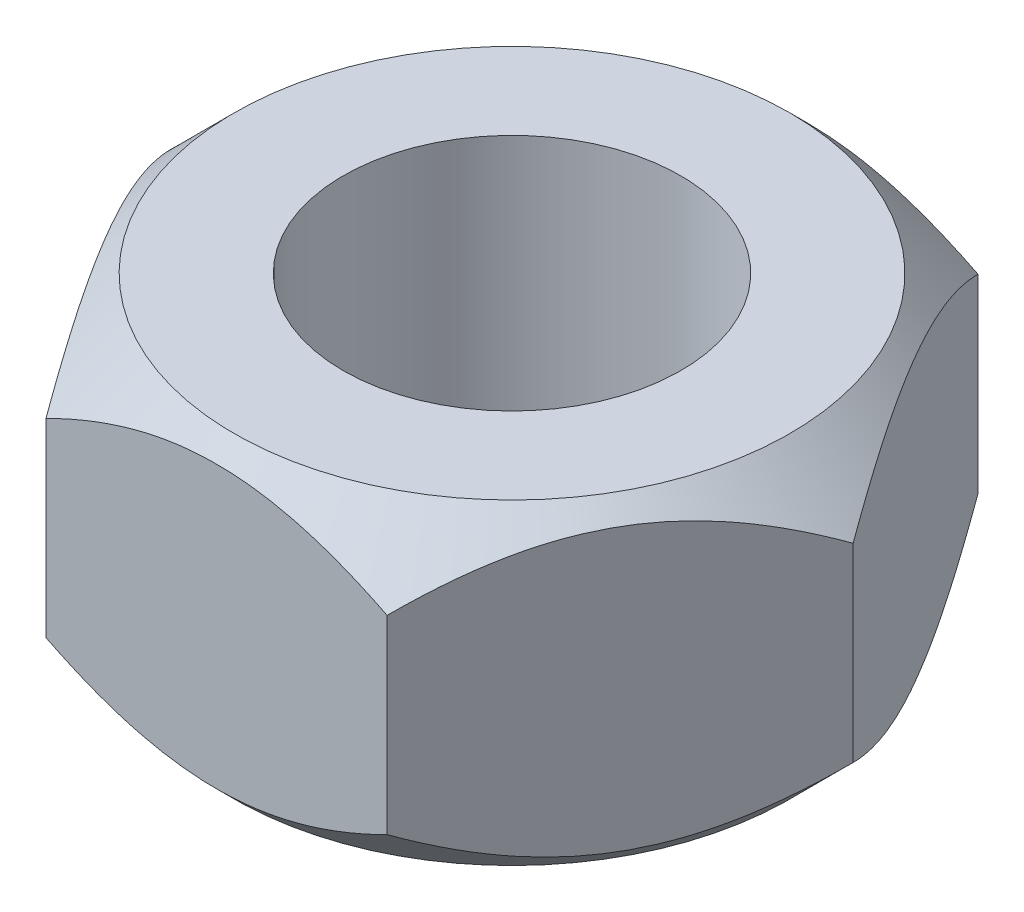
SolidWorks part; units mm, degrees
ref_plane "Front Plane" through (0, 0, 0) normal (0, 0, 1) x (1, 0, 0)
ref_plane "Top Plane" through (0, 0, 0) normal (0, 1, 0) x (1, 0, 0)
ref_plane "Right Plane" through (0, 0, 0) normal (1, 0, 0) x (0, 0, -1)
sketch "Sketch1" plane through (0, 0, 0) normal (0, 1, 0) x (1, 0, 0)
  line L1 (16.1658, 0) -> (8.0829, 14)
  line L2 (8.0829, 14) -> (-8.0829, 14)
  line L3 (-8.0829, 14) -> (-16.1658, 0)
  line L4 (-16.1658, 0) -> (-8.0829, -14)
  line L5 (-8.0829, -14) -> (8.0829, -14)
  line L6 (8.0829, -14) -> (16.1658, 0)
  circle A0 centre (0, 0) radius 14 construction
  circle A1 centre (0, 0) radius 8
  dimension "D2" = 16
  dimension "D1" = 28
extrude "Boss-Extrude1" add sketch "Sketch1" along normal mid plane 15
sketch "Sketch2" plane through (0, 0, 0) normal (0, 0, 1) x (1, 0, 0)
  line L0 (13.1658, 7.5) -> (16.1658, 4.5)
  line L1 (8.0829, 7.5) -> (16.1658, 7.5) construction
  line L2 (16.1658, 7.5) -> (16.1658, -7.5) construction
  line L3 (16.1658, 4.5) -> (16.1658, 7.5)
  line L4 (16.1658, 7.5) -> (13.1658, 7.5)
  line L5 (0, 0) -> (0, 11.2607) construction
  dimension "D1" = 3
  dimension "D2" = 3
revolve "Cut-Revolve1" cut sketch "Sketch2" angle 360 about L5
mirror "Mirror1" about plane through (0, 0, 0) normal (0, 1, 0) of "Cut-Revolve1"
